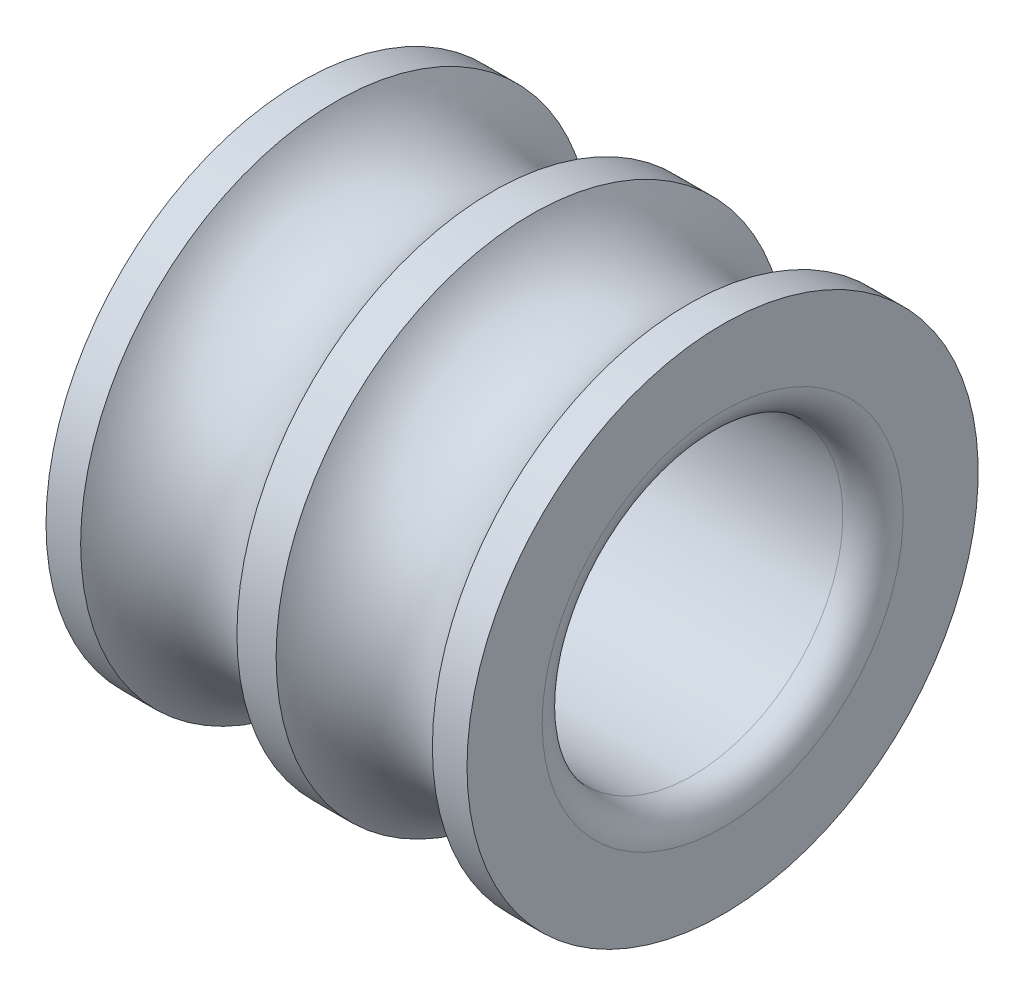
SolidWorks part; units mm, degrees
ref_plane "Plan1" through (0, 0, 0) normal (0, 0, 1) x (1, 0, 0)
ref_plane "Plan2" through (0, 0, 0) normal (0, 1, 0) x (1, 0, 0)
ref_plane "Plan3" through (0, 0, 0) normal (1, 0, 0) x (0, 0, -1)
sketch "Esquisse1" plane through (0, 0, 0) normal (0, 0, 1) x (1, 0, 0)
  line L0 (0, 0) -> (30.1449, 0) construction
  line L1 (0, 5) -> (14, 5)
  line L2 (14, 5) -> (14, 8.5)
  line L3 (14, 8.5) -> (12.8481, 8.5)
  line L4 (0, 8.5) -> (0, 5)
  line L5 (7.6519, 8.5) -> (6.3481, 8.5)
  line L6 (1.1519, 8.5) -> (0, 8.5)
  arc A0 (1.1519, 8.5) -> (6.3481, 8.5) centre (3.75, 10) ccw
  arc A1 (7.6519, 8.5) -> (12.8481, 8.5) centre (10.25, 10) ccw
  dimension "D1" = 6
  dimension "D2" = 10
  dimension "D6" = 6
  dimension "D7" = 6.5
  dimension "D8" = 3.75
  dimension "D3" = 14
  dimension "D4" = 5
  dimension "D5" = 3.5
revolve "Base-Révolution" add sketch "Esquisse1" angle 360 about L0
fillet "Congé1" radius 1 2 edges at (14, 0, 5) (0, 0, 5)
